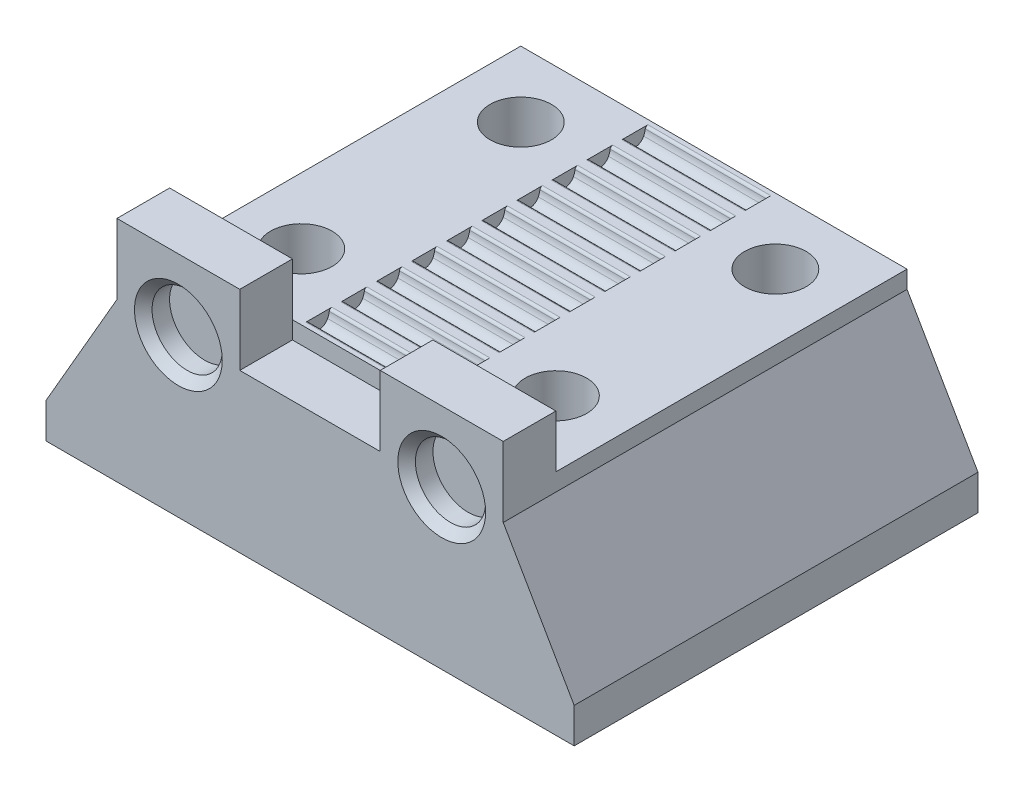
SolidWorks part; units mm, degrees
ref_plane "Piano frontale" through (0, 0, 0) normal (0, 0, 1) x (1, 0, 0)
ref_plane "Piano superiore" through (0, 0, 0) normal (0, 1, 0) x (1, 0, 0)
ref_plane "Piano destro" through (0, 0, 0) normal (1, 0, 0) x (0, 0, -1)
sketch "Schizzo1" plane through (0, 0, 0) normal (0, 0, 1) x (1, 0, 0)
  line L0 (0, 0) -> (0, -10) construction
  line L1 (11, -1) -> (11, 0)
  line L2 (11, 0) -> (-11, 0)
  line L3 (11, -1) -> (15.0415, -8)
  line L4 (15.0415, -8) -> (15.0415, -10)
  line L5 (-15.0415, -10) -> (15.0415, -10)
  line L6 (-15.0415, -8) -> (-15.0415, -10)
  line L7 (-11, -1) -> (-15.0415, -8)
  line L8 (-11, -1) -> (-11, 0)
  dimension "D1" = 150
  dimension "D2" = 1
  dimension "D3" = 11
  dimension "D4" = 2
  dimension "D5" = 10
extrude "Estrusione-Estrusione1" add sketch "Schizzo1" along normal mid plane 20
sketch "Schizzo2" plane through (0, 0, 0) normal (1, 0, 0) x (0, 0, -1)
  line L0 (-10, 0) -> (10, 0) construction
  line L1 (-10, 0) -> (10, 0) construction
  line L2 (-10, 0) -> (-9.7402, 0)
  line L3 (-9, 0) -> (-9, -0.75) construction
  line L4 (-8, 0) -> (-8.2598, 0)
  line L5 (-8, 0) -> (-7.7402, 0)
  line L6 (-6, 0) -> (-6.2598, 0)
  line L7 (-7, 0) -> (-7, -0.75) construction
  line L8 (-6, 0) -> (-5.7402, 0)
  line L9 (-4, 0) -> (-4.2598, 0)
  line L10 (-5, 0) -> (-5, -0.75) construction
  line L11 (-4, 0) -> (-3.7402, 0)
  line L12 (-2, 0) -> (-2.2598, 0)
  line L13 (-3, 0) -> (-3, -0.75) construction
  line L14 (-2, 0) -> (-1.7402, 0)
  line L15 (0, 0) -> (-0.2598, 0)
  line L16 (-1, 0) -> (-1, -0.75) construction
  line L17 (-10, 0) -> (-10, 1.4771)
  line L18 (-10, 1.4771) -> (10, 1.4771)
  line L19 (10, 1.4771) -> (10, 0)
  line L20 (0, 0) -> (0.2598, 0)
  line L21 (2, 0) -> (1.7402, 0)
  line L22 (1, 0) -> (1, -0.75) construction
  line L23 (2, 0) -> (2.2598, 0)
  line L24 (4, 0) -> (3.7402, 0)
  line L25 (3, 0) -> (3, -0.75) construction
  line L26 (4, 0) -> (4.2598, 0)
  line L27 (6, 0) -> (5.7402, 0)
  line L28 (5, 0) -> (5, -0.75) construction
  line L29 (6, 0) -> (6.2598, 0)
  line L30 (8, 0) -> (7.7402, 0)
  line L31 (7, 0) -> (7, -0.75) construction
  line L32 (8, 0) -> (8.2598, 0)
  line L33 (10, 0) -> (9.7402, 0)
  line L34 (9, 0) -> (9, -0.75) construction
  arc A0 (-9.5915, -0.1304) -> (-9.7402, 0) centre (-9.7402, -0.15) ccw
  arc A1 (-8.5011, -0.4382) -> (-9.4989, -0.4382) centre (-9, -0.195) cw
  arc A2 (-9.4989, -0.4382) -> (-9.5915, -0.1304) centre (-8.6, 0) cw
  arc A3 (-8.5011, -0.4382) -> (-8.4085, -0.1304) centre (-9.4, 0) ccw
  arc A4 (-8.4085, -0.1304) -> (-8.2598, 0) centre (-8.2598, -0.15) cw
  arc A5 (-7.5915, -0.1304) -> (-7.7402, 0) centre (-7.7402, -0.15) ccw
  arc A6 (-6.5011, -0.4382) -> (-7.4989, -0.4382) centre (-7, -0.195) cw
  arc A7 (-7.4989, -0.4382) -> (-7.5915, -0.1304) centre (-6.6, 0) cw
  arc A8 (-6.5011, -0.4382) -> (-6.4085, -0.1304) centre (-7.4, 0) ccw
  arc A9 (-6.4085, -0.1304) -> (-6.2598, 0) centre (-6.2598, -0.15) cw
  arc A10 (-5.5915, -0.1304) -> (-5.7402, 0) centre (-5.7402, -0.15) ccw
  arc A11 (-4.5011, -0.4382) -> (-5.4989, -0.4382) centre (-5, -0.195) cw
  arc A12 (-5.4989, -0.4382) -> (-5.5915, -0.1304) centre (-4.6, 0) cw
  arc A13 (-4.5011, -0.4382) -> (-4.4085, -0.1304) centre (-5.4, 0) ccw
  arc A14 (-4.4085, -0.1304) -> (-4.2598, 0) centre (-4.2598, -0.15) cw
  arc A15 (-3.5915, -0.1304) -> (-3.7402, 0) centre (-3.7402, -0.15) ccw
  arc A16 (-2.5011, -0.4382) -> (-3.4989, -0.4382) centre (-3, -0.195) cw
  arc A17 (-3.4989, -0.4382) -> (-3.5915, -0.1304) centre (-2.6, 0) cw
  arc A18 (-2.5011, -0.4382) -> (-2.4085, -0.1304) centre (-3.4, 0) ccw
  arc A19 (-2.4085, -0.1304) -> (-2.2598, 0) centre (-2.2598, -0.15) cw
  arc A20 (-1.5915, -0.1304) -> (-1.7402, 0) centre (-1.7402, -0.15) ccw
  arc A21 (-0.5011, -0.4382) -> (-1.4989, -0.4382) centre (-1, -0.195) cw
  arc A22 (-1.4989, -0.4382) -> (-1.5915, -0.1304) centre (-0.6, 0) cw
  arc A23 (-0.5011, -0.4382) -> (-0.4085, -0.1304) centre (-1.4, 0) ccw
  arc A24 (-0.4085, -0.1304) -> (-0.2598, 0) centre (-0.2598, -0.15) cw
  arc A25 (0.4085, -0.1304) -> (0.2598, 0) centre (0.2598, -0.15) ccw
  arc A26 (1.4989, -0.4382) -> (0.5011, -0.4382) centre (1, -0.195) cw
  arc A27 (0.5011, -0.4382) -> (0.4085, -0.1304) centre (1.4, 0) cw
  arc A28 (1.4989, -0.4382) -> (1.5915, -0.1304) centre (0.6, 0) ccw
  arc A29 (1.5915, -0.1304) -> (1.7402, 0) centre (1.7402, -0.15) cw
  arc A30 (2.4085, -0.1304) -> (2.2598, 0) centre (2.2598, -0.15) ccw
  arc A31 (3.4989, -0.4382) -> (2.5011, -0.4382) centre (3, -0.195) cw
  arc A32 (2.5011, -0.4382) -> (2.4085, -0.1304) centre (3.4, 0) cw
  arc A33 (3.4989, -0.4382) -> (3.5915, -0.1304) centre (2.6, 0) ccw
  arc A34 (3.5915, -0.1304) -> (3.7402, 0) centre (3.7402, -0.15) cw
  arc A35 (4.4085, -0.1304) -> (4.2598, 0) centre (4.2598, -0.15) ccw
  arc A36 (5.4989, -0.4382) -> (4.5011, -0.4382) centre (5, -0.195) cw
  arc A37 (4.5011, -0.4382) -> (4.4085, -0.1304) centre (5.4, 0) cw
  arc A38 (5.4989, -0.4382) -> (5.5915, -0.1304) centre (4.6, 0) ccw
  arc A39 (5.5915, -0.1304) -> (5.7402, 0) centre (5.7402, -0.15) cw
  arc A40 (6.4085, -0.1304) -> (6.2598, 0) centre (6.2598, -0.15) ccw
  arc A41 (7.4989, -0.4382) -> (6.5011, -0.4382) centre (7, -0.195) cw
  arc A42 (6.5011, -0.4382) -> (6.4085, -0.1304) centre (7.4, 0) cw
  arc A43 (7.4989, -0.4382) -> (7.5915, -0.1304) centre (6.6, 0) ccw
  arc A44 (7.5915, -0.1304) -> (7.7402, 0) centre (7.7402, -0.15) cw
  arc A45 (8.4085, -0.1304) -> (8.2598, 0) centre (8.2598, -0.15) ccw
  arc A46 (9.4989, -0.4382) -> (8.5011, -0.4382) centre (9, -0.195) cw
  arc A47 (8.5011, -0.4382) -> (8.4085, -0.1304) centre (9.4, 0) cw
  arc A48 (9.4989, -0.4382) -> (9.5915, -0.1304) centre (8.6, 0) ccw
  arc A49 (9.5915, -0.1304) -> (9.7402, 0) centre (9.7402, -0.15) cw
  point P9 (-8.6, 0)
  point P26 (-6.6, 0)
  point P42 (-4.6, 0)
  point P58 (-2.6, 0)
  point P74 (-0.6, 0)
  point P88 (1.4, 0)
  point P104 (3.4, 0)
  point P120 (5.4, 0)
  point P136 (7.4, 0)
  point P152 (9.4, 0)
  dimension "D3" = 0.4
  dimension "D4" = 1
  dimension "D5" = 0.75
  dimension "D1" = 0.15
  dimension "D2" = 0.555
  dimension "D6" = 1
  dimension "D7" = 10
  dimension "D8" = 2
extrude "Taglio-Estrusione6" cut sketch "Schizzo2" against normal mid plane 7 contours A23 A24 L15 L19 L18 L17 L2 A0 A2 A1 A3 A4 L4 L5 A5 A7 A6 A8 A9 L6 L8 A10 A12 A11 A13 A14 L9 L11 A15 A17 A16 A18 A19 L12 L14 A20 A22 A21
sketch "Schizzo3" plane through (0, 0, 0) normal (0, 1, 0) x (1, 0, 0)
  line L1 (-7.25, -6.25) -> (7.25, -6.25) construction
  line L2 (-7.25, -6.25) -> (-7.25, 6.25) construction
  line L3 (-7.25, 6.25) -> (7.25, 6.25) construction
  line L4 (7.25, -6.25) -> (7.25, 6.25) construction
  line L5 (-7.25, -6.25) -> (7.25, 6.25) construction
  line L6 (-7.25, 6.25) -> (7.25, -6.25) construction
  line L9 (11, -10) -> (11, 10) construction
  line L10 (11, -10) -> (-11, -10) construction
  circle A0 centre (7.25, 6.25) radius 1.75
  circle A1 centre (7.25, -6.25) radius 1.75
  circle A2 centre (-7.25, -6.25) radius 1.75
  circle A3 centre (-7.25, 6.25) radius 1.75
  point P0 (0, 0)
  dimension "D1" = 3.5
  dimension "D3" = 3.75
  dimension "D2" = 3.75
extrude "Taglio-Estrusione7" cut sketch "Schizzo3" against normal through all
sketch "Schizzo4" plane through (0, 0, 10) normal (0, 0, 1) x (1, 0, 0)
  line L0 (-15.0415, -10) -> (15.0415, -10) construction
  line L1 (-15.0415, -8) -> (-15.0415, -10) construction
  line L2 (-11, -1) -> (-15.0415, -8) construction
  line L3 (15.0415, -10) -> (15.0415, -8) construction
  line L4 (15.0415, -8) -> (11, -1) construction
  line L5 (-15.0415, -10) -> (15.0415, -10)
  line L6 (-15.0415, -8) -> (-15.0415, -10)
  line L7 (-11, -1) -> (-15.0415, -8)
  line L8 (15.0415, -10) -> (15.0415, -8)
  line L9 (15.0415, -8) -> (11, -1)
  line L10 (-11, 0) -> (-11, -1) construction
  line L12 (11, -1) -> (11, 0) construction
  line L14 (-4.0052, -1) -> (3.9948, -1)
  line L15 (11, 0) -> (-11, 0) construction
  line L16 (-11, 3) -> (-4.0052, 3)
  line L17 (-4.0052, 3) -> (-4.0052, -1)
  line L18 (3.9948, -1) -> (3.9948, 3)
  line L19 (3.9948, 3) -> (11, 3)
  line L20 (-11, 3) -> (-11, -1)
  line L21 (11, -1) -> (11, 3)
  point P4 (0, 1.5)
  point P20 (0, 0)
  dimension "D1" = 8
  dimension "D2" = 3
  dimension "D3" = 1
extrude "Estrusione-Estrusione2" add sketch "Schizzo4" along normal blind 3
sketch "Schizzo5" plane through (0, 0, 13) normal (0, 0, 1) x (1, 0, 0)
  line L0 (11, -1) -> (3.9948, -1) construction
  line L1 (11, -1) -> (3.9948, -1) construction
  line L2 (-4.0052, -1) -> (-11, -1) construction
  line L3 (-4.0052, -1) -> (-11, -1) construction
  circle A0 centre (7.4974, -1) radius 2
  circle A1 centre (-7.5026, -1) radius 2
  dimension "D1" = 4
extrude "Taglio-Estrusione8" cut sketch "Schizzo5" against normal blind 1.5
chamfer "Smusso2" distance 0.5 angle 45 2 edges at (-5.5026, -1, 13) (9.4974, -1, 13)
sketch "Schizzo6" plane through (0, -10, 0) normal (0, -1, 0) x (1, 0, 0)
  line L1 (-8.9, 9.1079) -> (-10.55, 6.25)
  line L2 (-10.55, 6.25) -> (-8.9, 3.3921)
  line L3 (-8.9, 3.3921) -> (-5.6, 3.3921)
  line L4 (-5.6, 3.3921) -> (-3.95, 6.25)
  line L5 (-3.95, 6.25) -> (-5.6, 9.1079)
  line L6 (-5.6, 9.1079) -> (-8.9, 9.1079)
  line L7 (-5.6, -3.3921) -> (-8.9, -3.3921)
  line L8 (-8.9, -3.3921) -> (-10.55, -6.25)
  line L9 (-10.55, -6.25) -> (-8.9, -9.1079)
  line L10 (-8.9, -9.1079) -> (-5.6, -9.1079)
  line L11 (-5.6, -9.1079) -> (-3.95, -6.25)
  line L12 (-3.95, -6.25) -> (-5.6, -3.3921)
  line L13 (10.55, -6.25) -> (8.9, -3.3921)
  line L14 (8.9, -3.3921) -> (5.6, -3.3921)
  line L15 (5.6, -3.3921) -> (3.95, -6.25)
  line L16 (3.95, -6.25) -> (5.6, -9.1079)
  line L17 (5.6, -9.1079) -> (8.9, -9.1079)
  line L18 (8.9, -9.1079) -> (10.55, -6.25)
  line L19 (5.6, 3.3921) -> (8.9, 3.3921)
  line L20 (8.9, 3.3921) -> (10.55, 6.25)
  line L21 (10.55, 6.25) -> (8.9, 9.1079)
  line L22 (8.9, 9.1079) -> (5.6, 9.1079)
  line L23 (5.6, 9.1079) -> (3.95, 6.25)
  line L24 (3.95, 6.25) -> (5.6, 3.3921)
  circle A0 centre (7.25, 6.25) radius 1.75 construction
  circle A1 centre (7.25, -6.25) radius 1.75 construction
  circle A2 centre (-7.25, -6.25) radius 1.75 construction
  circle A3 centre (-7.25, 6.25) radius 1.75 construction
  circle A4 centre (7.25, 6.25) radius 1.75 construction
  circle A5 centre (7.25, -6.25) radius 1.75 construction
  circle A6 centre (-7.25, -6.25) radius 1.75 construction
  circle A7 centre (-7.25, 6.25) radius 1.75 construction
  circle A8 centre (-7.25, 6.25) radius 2.8579 construction
  circle A9 centre (-7.25, -6.25) radius 2.8579 construction
  circle A10 centre (7.25, -6.25) radius 2.8579 construction
  circle A11 centre (7.25, 6.25) radius 2.8579 construction
  dimension "D1" = 6.6
extrude "Taglio-Estrusione9" cut sketch "Schizzo6" against normal blind 3.5
